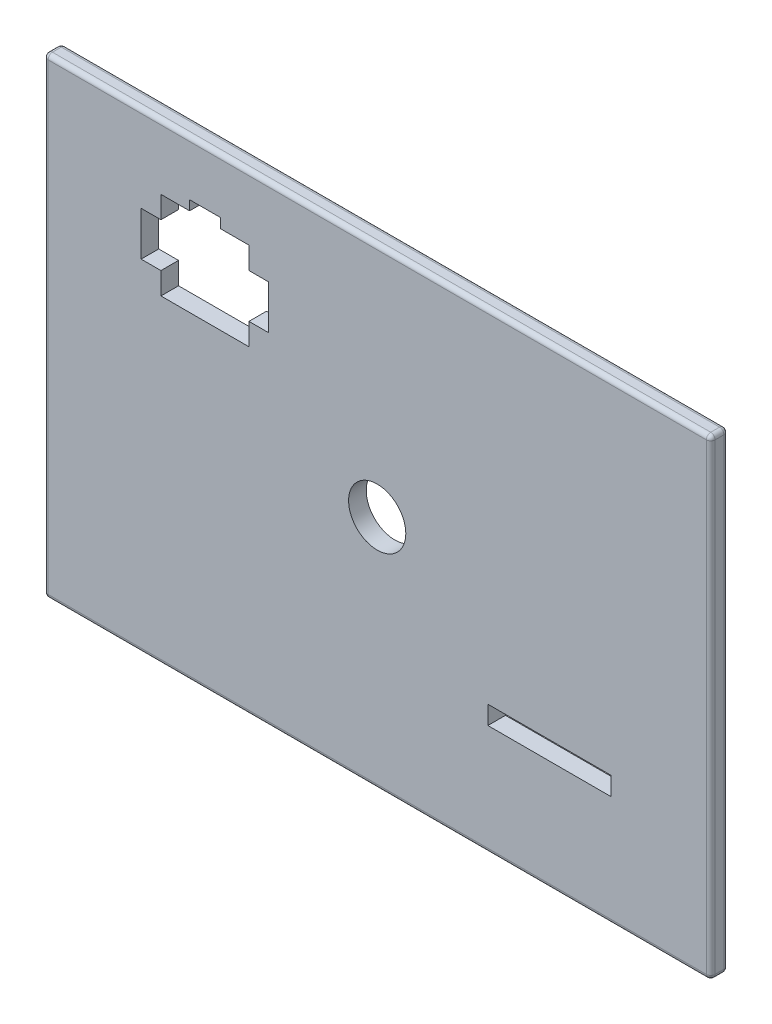
SolidWorks part; units mm, degrees
ref_plane "Front Plane" through (0, 0, 0) normal (0, 0, 1) x (1, 0, 0)
ref_plane "Top Plane" through (0, 0, 0) normal (0, 1, 0) x (1, 0, 0)
ref_plane "Right Plane" through (0, 0, 0) normal (1, 0, 0) x (0, 0, -1)
sketch "Sketch1" plane through (0, 0, 0) normal (0, 0, 1) x (1, 0, 0)
  line L1 (-37.9, -26.8) -> (37.9, -26.8)
  line L2 (-37.9, -26.8) -> (-37.9, 26.8)
  line L3 (-37.9, 26.8) -> (37.9, 26.8)
  line L4 (37.9, -26.8) -> (37.9, 26.8)
  line L5 (-37.9, -26.8) -> (37.9, 26.8) construction
  line L6 (-37.9, 26.8) -> (37.9, -26.8) construction
  point P0 (0, 0)
  dimension "D1" = 75.8
  dimension "D2" = 53.6
extrude "Boss-Extrude1" add sketch "Sketch1" along normal blind 2
sketch "Sketch5" plane through (0, 0, 2) normal (0, 0, 1) x (1, 0, 0)
  line L0 (-37.9, 26.8) -> (-37.9, -26.8) construction
  line L1 (-14.575, 9.475) -> (-24.575, 9.475)
  line L2 (-14.575, 9.475) -> (-14.575, 19.475)
  line L3 (-14.575, 19.475) -> (-24.575, 19.475)
  line L4 (-24.575, 9.475) -> (-24.575, 19.475)
  line L5 (-14.575, 9.475) -> (-24.575, 19.475) construction
  line L6 (-14.575, 19.475) -> (-24.575, 9.475) construction
  line L7 (-12.325, 11.975) -> (-26.825, 11.975)
  line L8 (-12.325, 11.975) -> (-12.325, 16.975)
  line L9 (-12.325, 16.975) -> (-26.825, 16.975)
  line L10 (-26.825, 11.975) -> (-26.825, 16.975)
  line L11 (-12.325, 11.975) -> (-26.825, 16.975) construction
  line L12 (-12.325, 16.975) -> (-26.825, 11.975) construction
  line L13 (-21.325, 20.575) -> (-17.825, 20.575)
  line L14 (-21.325, 20.575) -> (-21.325, 14.475)
  line L15 (-21.325, 14.475) -> (-17.825, 14.475)
  line L16 (-17.825, 20.575) -> (-17.825, 14.475)
  line L17 (12.575, -12.125) -> (26.575, -12.125)
  line L18 (12.575, -12.125) -> (12.575, -14.225)
  line L19 (12.575, -14.225) -> (26.575, -14.225)
  line L20 (26.575, -12.125) -> (26.575, -14.225)
  line L21 (-35.9, 26.8) -> (35.9, 26.8) construction
  line L22 (-35.9, 26.8) -> (-35.9, -24.8) construction
  line L23 (-35.9, -24.8) -> (35.9, -24.8) construction
  line L24 (35.9, 26.8) -> (35.9, -24.8) construction
  line L25 (4, 3.25) -> (4, -20.75) construction
  line L26 (37.9, -26.8) -> (37.9, 26.8) construction
  line L27 (-37.9, -26.8) -> (37.9, -26.8) construction
  line L28 (37.9, 26.8) -> (-37.9, 26.8) construction
  line L29 (10.575, -14.225) -> (28.575, -14.225) construction
  line L34 (10.575, -14.225) -> (10.575, -15.925) construction
  line L35 (10.575, -15.925) -> (28.575, -15.925) construction
  line L36 (28.575, -14.225) -> (28.575, -15.925) construction
  line L37 (4, -20.75) -> (0, -20.75) construction
  line L38 (0, -20.75) -> (0, 3.25) construction
  line L39 (0, 3.25) -> (4, 3.25) construction
  line L40 (-3.25, 0) -> (-3.25, 14.475) construction
  line L41 (-35.9, 14.475) -> (-26.825, 14.475) construction
  line L42 (-3.25, 14.475) -> (-12.325, 14.475) construction
  line L43 (0, -3.25) -> (35.9, -3.25) construction
  line L44 (26.575, -13.175) -> (35.9, -13.175) construction
  line L45 (0, 3.25) -> (-35.9, 3.25) construction
  line L46 (12.575, -13.175) -> (3.25, -13.175) construction
  line L47 (3.25, -13.175) -> (3.25, 0) construction
  line L48 (-19.575, 9.475) -> (-19.575, 3.25) construction
  line L49 (-19.575, 20.575) -> (-19.575, 26.8) construction
  line L50 (19.575, -15.925) -> (19.575, -24.8) construction
  line L51 (19.575, -12.125) -> (19.575, -3.25) construction
  circle A1 centre (0, 0) radius 3.25
  point P0 (-19.575, 14.475)
  point P6 (-19.575, 14.475)
  point P26 (19.575, -14.225)
  dimension "D19" = 6.5
  dimension "D1" = 5
  dimension "D2" = 10
  dimension "D3" = 3.5
  dimension "D4" = 1.1
  dimension "D5" = 14.5
  dimension "D6" = 10
  dimension "D8" = 2.1
  dimension "D9" = 14
  dimension "D10" = 2
  dimension "D12" = 2
  dimension "D13" = 2
  dimension "D15" = 18
  dimension "D16" = 1.7
  dimension "D17" = 4
  dimension "D18" = 24
extrude "Cut-Extrude1" cut sketch "Sketch5" against normal through all contours A1 | L20 L17 L18 L19 | L10 L7 L4 L9 | L14 L3 L4 L9 | L16 L3 L14 L9
fillet "Fillet1" radius 0.5 12 edges at (0, -26.8, 2) (0, -26.8, 0) (-37.9, 0, 2) (-37.9, -26.8, 1) (-37.9, 0, 0) (0, 26.8, 2) (-37.9, 26.8, 1) (0, 26.8, 0) (37.9, -26.8, 1) (37.9, 0, 2) (37.9, 26.8, 1) (37.9, 0, 0)
